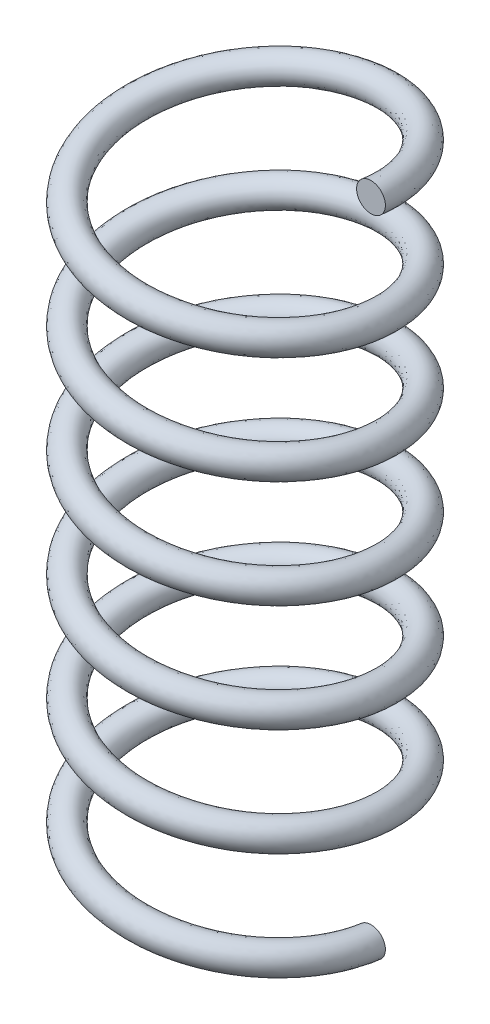
SolidWorks part; units mm, degrees
ref_plane "Front Plane" through (0, 0, 0) normal (0, 0, 1) x (1, 0, 0)
ref_plane "Top Plane" through (0, 0, 0) normal (0, 1, 0) x (1, 0, 0)
ref_plane "Right Plane" through (0, 0, 0) normal (1, 0, 0) x (0, 0, -1)
sketch "Sketch1" plane through (0, 0, 0) normal (1, 0, 0) x (0, 0, -1)
  line L0 (0, 0) -> (0, 4.9624) construction
  line L2 (1.2768, 4.9624) -> (3.7644, 4.9624) construction
  dimension "D1" = 4.9624
sketch "Sketch2" plane through (0, 0, 0) normal (0, 1, 0) x (1, 0, 0)
  circle A0 centre (0, 0) radius 2.625
  dimension "D1" = 5.25
curve "Helix/Spiral1"
sketch "Sketch3" plane through (0, 0, 0) normal (0, 1, 0) x (1, 0, 0)
  arc A0 (9.9705, 0) -> (5.8804, 2.7912) centre (6.973, 0) cw
sketch "Sketch4" plane through (0, 0, 0) normal (0, 0, 1) x (1, 0, 0)
  circle A0 centre (2.625, 0) radius 0.3
  spline S0 degree 3 poles (2.625, 0) (2.625, 0.0463) (2.4883, 0.14) (1.9045, 0.2797) (1.0307, 0.4196) (0, 0.5595) (-1.0307, 0.6993) (-1.9045, 0.8392) (-2.4883, 0.9791) (-2.6933, 1.1189) (-2.4883, 1.2588) (-1.9045, 1.3986) (-1.0307, 1.5385) (0, 1.6784) (1.0307, 1.8182) (1.9045, 1.9581) (2.4883, 2.098) (2.6933, 2.2378) (2.4883, 2.3777) (1.9045, 2.5176) (1.0307, 2.6574) (0, 2.7973) (-1.0307, 2.9372) (-1.9045, 3.077) (-2.4883, 3.2169) (-2.6933, 3.3568) (-2.4883, 3.4966) (-1.9045, 3.6365) (-1.0307, 3.7764) (0, 3.9162) (1.0307, 4.0561) (1.9045, 4.1959) (2.4883, 4.3358) (2.6933, 4.4757) (2.4883, 4.6155) (1.9045, 4.7554) (1.0307, 4.8953) (0, 5.0351) (-1.0307, 5.175) (-1.9045, 5.3149) (-2.4883, 5.4547) (-2.6933, 5.5946) (-2.4883, 5.7345) (-1.9045, 5.8743) (-1.0307, 6.0142) (0, 6.1541) (1.0307, 6.2939) (1.9045, 6.4338) (2.4883, 6.5736) (2.6933, 6.7135) (2.4883, 6.8534) (1.9045, 6.9932) (1.0307, 7.1331) (0, 7.273) (-1.0307, 7.4128) (-1.9045, 7.5527) (-2.4883, 7.6926) (-2.6933, 7.8324) (-2.4883, 7.9723) (-1.9045, 8.1122) (-1.0307, 8.252) (0, 8.3919) (1.0307, 8.5318) (1.9045, 8.6716) (2.4883, 8.8115) (2.6933, 8.9514) (2.4883, 9.0912) (1.9045, 9.2311) (1.0307, 9.3709) (0, 9.5108) (-1.0307, 9.6507) (-1.9045, 9.7905) (-2.4883, 9.9304) (-2.6933, 10.0703) (-2.4883, 10.2101) (-1.9045, 10.35) (-1.0307, 10.4899) (0, 10.6297) (1.0307, 10.7696) (1.9045, 10.9095) (2.4883, 11.0493) (2.6933, 11.1892) (2.4883, 11.3291) (1.9045, 11.4689) (1.0307, 11.6088) (0, 11.7486) (-1.0307, 11.8885) (-1.9045, 12.0284) (-2.4883, 12.1682) (-2.6933, 12.3081) (-2.4883, 12.448) (-1.9045, 12.5878) (-1.0307, 12.7277) (0, 12.8676) (1.0307, 13.0074) (1.9045, 13.1473) (2.4883, 13.287) (2.625, 13.3807) (2.625, 13.427) knots 0 0 0 0 0.010417 0.020833 0.03125 0.041667 0.052083 0.0625 0.072917 0.083333 0.09375 0.104167 0.114583 0.125 0.135417 0.145833 0.15625 0.166667 0.177083 0.1875 0.197917 0.208333 0.21875 0.229167 0.239583 0.25 0.260417 0.270833 0.28125 0.291667 0.302083 0.3125 0.322917 0.333333 0.34375 0.354167 0.364583 0.375 0.385417 0.395833 0.40625 0.416667 0.427083 0.4375 0.447917 0.458333 0.46875 0.479167 0.489583 0.5 0.510417 0.520833 0.53125 0.541667 0.552083 0.5625 0.572917 0.583333 0.59375 0.604167 0.614583 0.625 0.635417 0.645833 0.65625 0.666667 0.677083 0.6875 0.697917 0.708333 0.71875 0.729167 0.739583 0.75 0.760417 0.770833 0.78125 0.791667 0.802083 0.8125 0.822917 0.833333 0.84375 0.854167 0.864583 0.875 0.885417 0.895833 0.90625 0.916667 0.927083 0.9375 0.947917 0.958333 0.96875 0.979167 0.989583 1 1 1 1 construction
  dimension "D1" = 0.6
sweep "Sweep1" add profiles "Sketch4" path "Helix/Spiral1"
equation "\"spring height\"= 17.5"
equation "\"D3@Helix/Spiral1\"    = \"height spring@Sketch1\""
equation "\"spring revolutions\"= 6"
equation "\"D5@Helix/Spiral1\"=\"spring revolutions\""
